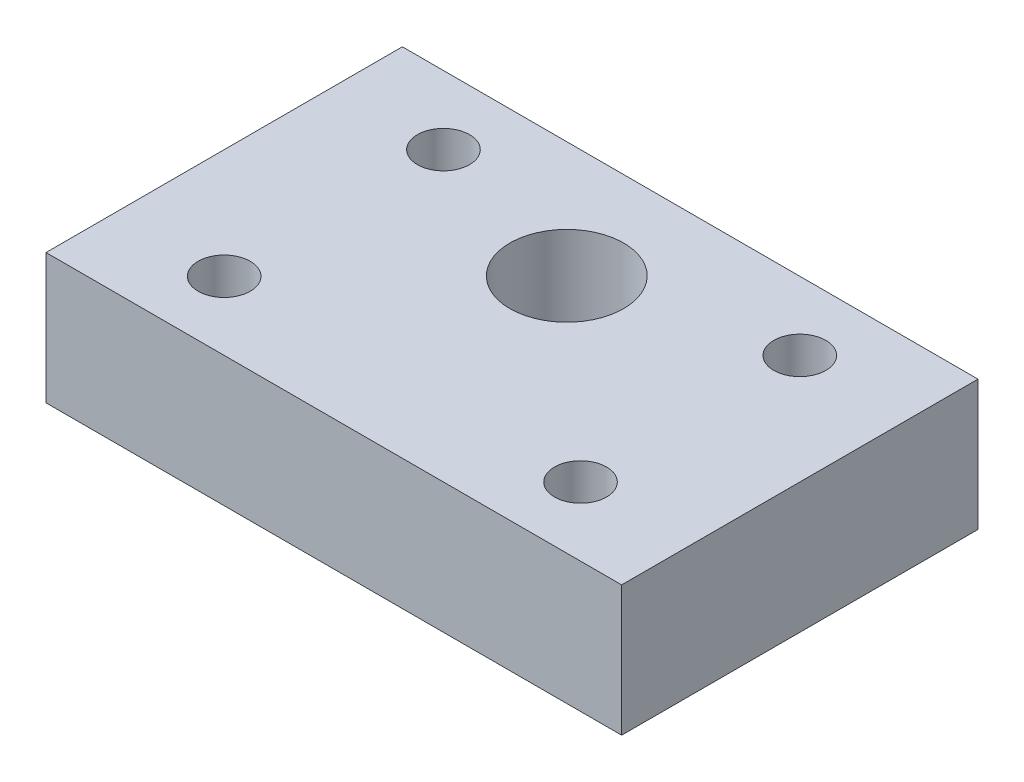
SolidWorks part; units mm, degrees
ref_plane "前视基准面" through (0, 0, 0) normal (0, 0, 1) x (1, 0, 0)
ref_plane "上视基准面" through (0, 0, 0) normal (0, 1, 0) x (1, 0, 0)
ref_plane "右视基准面" through (0, 0, 0) normal (1, 0, 0) x (0, 0, -1)
sketch "草图1" plane through (0, 0, 0) normal (0, 1, 0) x (1, 0, 0)
  line L1 (0, 0) -> (42, 0)
  line L2 (0, 0) -> (0, -26)
  line L3 (0, -26) -> (42, -26)
  line L4 (42, 0) -> (42, -26)
  dimension "D1" = 42
  dimension "D2" = 26
extrude "凸台-拉伸1" add sketch "草图1" along normal blind 9.5
sketch "草图3" plane through (0, 9.5, 0) normal (0, 1, 0) x (1, 0, 0)
  circle A0 centre (20.47, -8.4738) radius 4.15
  dimension "D1" = 8.3
extrude "切除-拉伸1" cut sketch "草图3" against normal through all
sketch "草图4" plane through (0, 9.5, 0) normal (0, 1, 0) x (1, 0, 0)
  line L0 (42, 0) -> (0, 0) construction
  line L1 (0, 0) -> (0, -26) construction
  line L2 (0, -26) -> (42, -26) construction
  line L3 (42, -26) -> (42, 0) construction
  circle A0 centre (8, -5) radius 1.9
  circle A1 centre (8, -21) radius 1.9
  circle A2 centre (34, -5) radius 1.9
  circle A3 centre (34, -21) radius 1.9
  dimension "D1" = 3.8
  dimension "D2" = 5
  dimension "D3" = 8
  dimension "D4" = 8
  dimension "D5" = 5
  dimension "D6" = 8
  dimension "D7" = 8
  dimension "D8" = 5
  dimension "D9" = 5
extrude "切除-拉伸2" cut sketch "草图4" against normal through all
